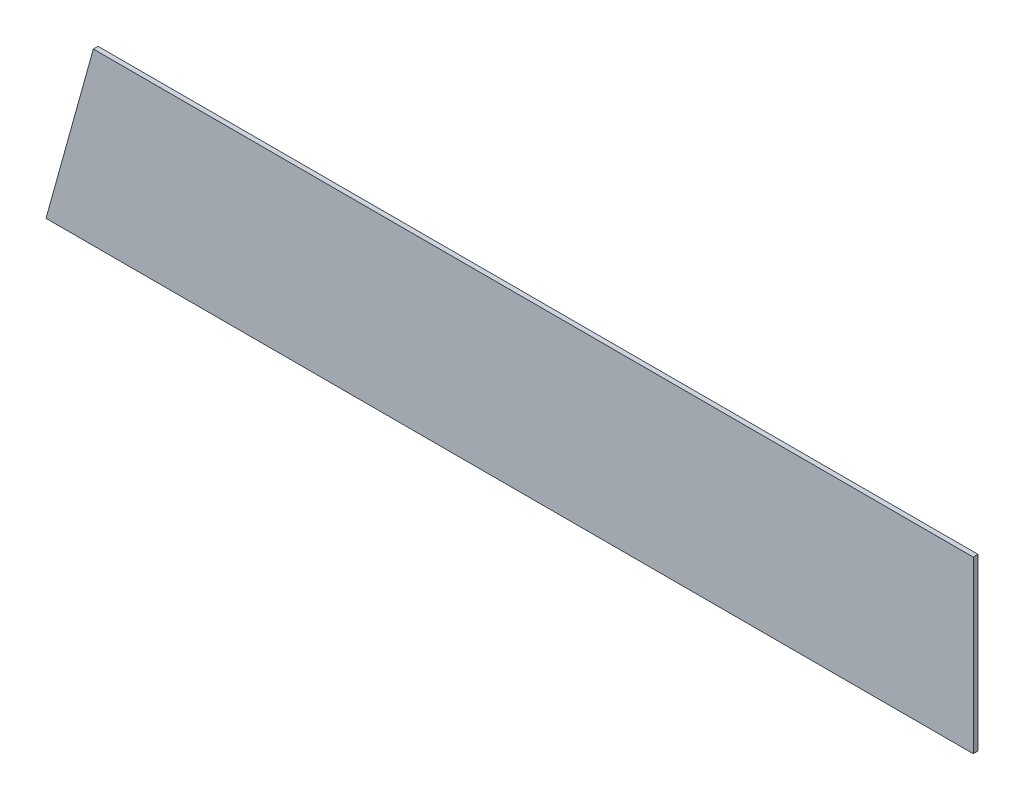
SolidWorks part; units mm, degrees
material "AISI Type A2 Tool Steel"
ref_plane "Front Plane" through (0, 0, 0) normal (0, 0, 1) x (1, 0, 0)
ref_plane "Top Plane" through (0, 0, 0) normal (0, 1, 0) x (1, 0, 0)
ref_plane "Right Plane" through (0, 0, 0) normal (1, 0, 0) x (0, 0, -1)
sketch "Croquis1" plane through (0, 0, 0) normal (0, 0, 1) x (1, 0, 0)
  line L1 (-38.9906, 8.2783) -> (54.0094, 8.2783)
  line L6 (54.0094, 8.2783) -> (54.0094, -9.7217)
  line L7 (54.0094, -9.7217) -> (-43.9906, -9.7217)
  line L8 (-38.9906, 8.2783) -> (-43.9906, -9.7217)
  point P0 (0, 0)
  dimension "D1" = 5
  dimension "D2" = 18
  dimension "D3" = 98
extrude "Saliente-Extruir1" add sketch "Croquis1" along normal blind 0.5
